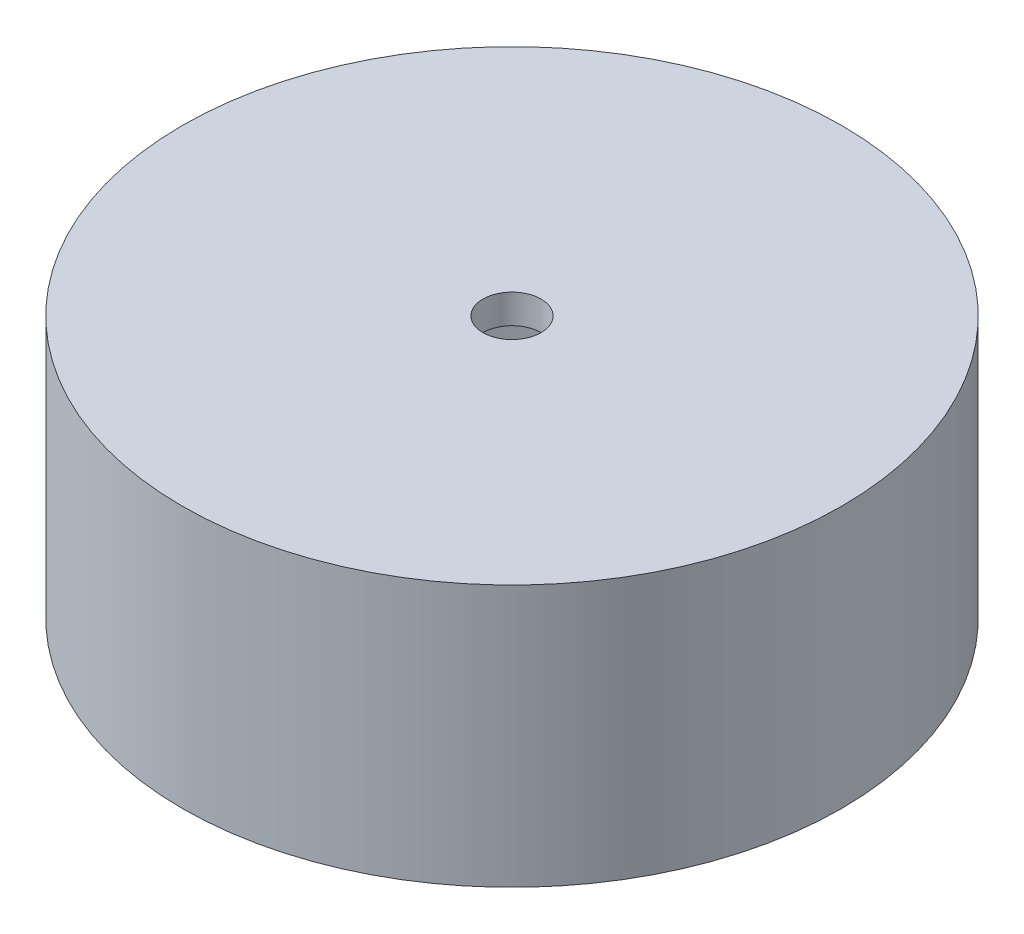
SolidWorks part; units mm, degrees
material "ABS"
ref_plane "Front Plane" through (0, 0, 0) normal (0, 0, 1) x (1, 0, 0)
ref_plane "Top Plane" through (0, 0, 0) normal (0, 1, 0) x (1, 0, 0)
ref_plane "Right Plane" through (0, 0, 0) normal (1, 0, 0) x (0, 0, -1)
sketch "Sketch1" plane through (0, 0, 0) normal (0, 1, 0) x (1, 0, 0)
  circle A0 centre (0, 0) radius 7
  circle A1 centre (0, 0) radius 8.5
  dimension "D1" = 14
  dimension "D2" = 1.5
extrude "Boss-Extrude1" add sketch "Sketch1" along normal blind 6
sketch "Sketch2" plane through (0, 6, 0) normal (0, 1, 0) x (1, 0, 0)
  circle A0 centre (0, 0) radius 8.5 construction
  circle A1 centre (0, 0) radius 8.5
extrude "Boss-Extrude2" add sketch "Sketch2" along normal blind 0.75
sketch "Sketch3" plane through (0, 6.75, 0) normal (0, 1, 0) x (1, 0, 0)
  circle A0 centre (0, 0) radius 0.75
  circle A1 centre (0, 0) radius 8.5
  circle A2 centre (0, 0) radius 8.5 construction
  dimension "D2" = 1.5
  dimension "D1" = 0
extrude "Cut-Extrude1" cut sketch "Sketch3" against normal through all both and the other way through all
fillet "Fillet1" radius 0.5 1 edges at (0, 0, 7)
